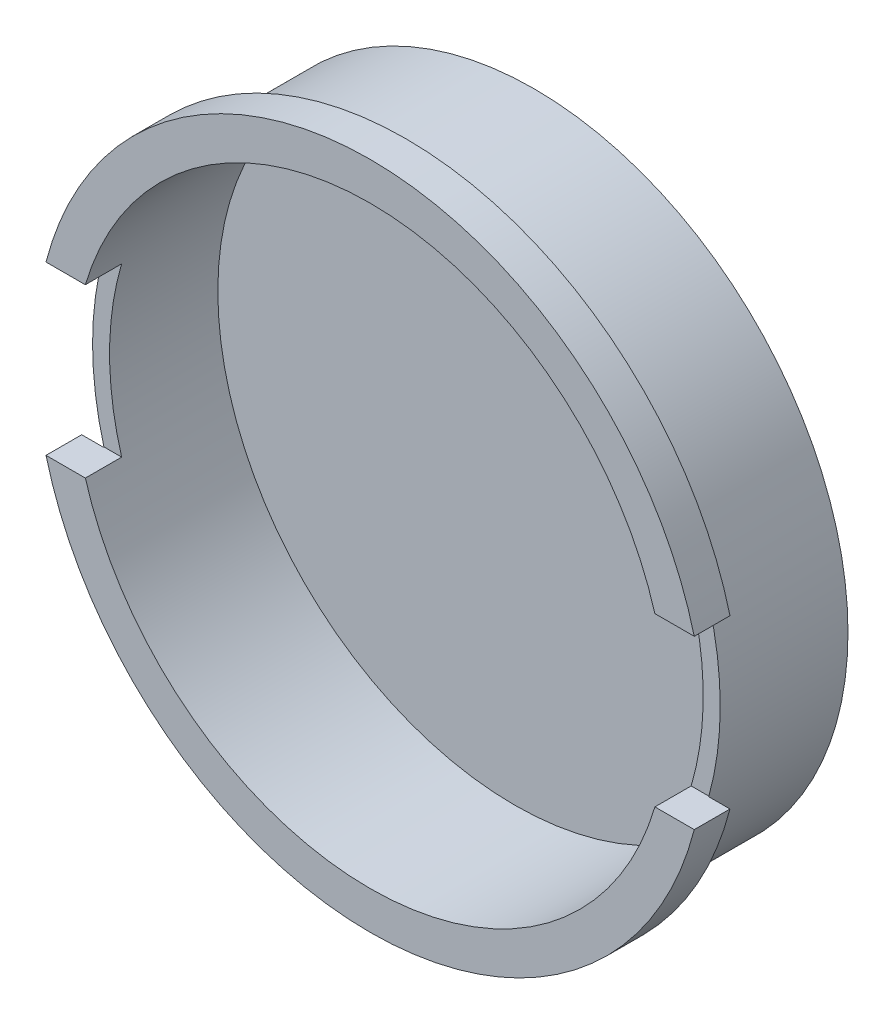
SolidWorks part; units mm, degrees
material "Chrome Stainless Steel"
ref_plane "Front Plane" through (0, 0, 0) normal (0, 0, 1) x (1, 0, 0)
ref_plane "Top Plane" through (0, 0, 0) normal (0, 1, 0) x (1, 0, 0)
ref_plane "Right Plane" through (0, 0, 0) normal (1, 0, 0) x (0, 0, -1)
sketch "Sketch1" plane through (0, 0, 0) normal (0, 0, 1) x (1, 0, 0)
  circle A0 centre (0, 0) radius 14.2875
  dimension "D1" = 28.575
extrude "Boss-Extrude1" add sketch "Sketch1" along normal blind 0.889
sketch "Sketch2" plane through (0, 0, 0.889) normal (0, 0, 1) x (1, 0, 0)
  circle A0 centre (0, 0) radius 13.5128
  circle A1 centre (0, 0) radius 14.2875
  dimension "D1" = 27.0256
  dimension "D2" = 28.575
extrude "Boss-Extrude2" add sketch "Sketch2" along normal blind 4.953
sketch "Sketch3" plane through (0, 0, 5.842) normal (0, 0, 1) x (1, 0, 0)
  circle A0 centre (0, 0) radius 15.24
  circle A1 centre (0, 0) radius 13.5128
extrude "Boss-Extrude3" add sketch "Sketch3" along normal blind 1.6256
sketch "Sketch4" plane through (0, 0, 7.4676) normal (0, 0, 1) x (1, 0, 0)
  line L1 (-19.05, 3.81) -> (19.05, 3.81)
  line L2 (-19.05, 3.81) -> (-19.05, -3.81)
  line L3 (-19.05, -3.81) -> (19.05, -3.81)
  line L4 (19.05, 3.81) -> (19.05, -3.81)
  line L5 (-19.05, 3.81) -> (19.05, -3.81) construction
  line L6 (-19.05, -3.81) -> (19.05, 3.81) construction
  point P0 (0, 0)
  dimension "D1" = 38.1
  dimension "D2" = 7.62
extrude "Cut-Extrude1" cut sketch "Sketch4" against normal blind 1.651
sketch "Sketch5" plane through (0, 0, 7.4426) normal (0, 0, 1) x (1, 0, 0)
  line L0 (-0.8, 12.3) -> (-0.8, 13.1) construction
  line L1 (0.8, 13.1) -> (0.8, 12.3) construction
  line L2 (-2.1761, 0.4523) -> (-2.7495, 3.7042)
  line L3 (-3.3999, 3.5895) -> (-2.8265, 0.3376)
  line L4 (-2.1761, 0.4523) -> (-2.7495, 3.7042)
  line L5 (-3.3999, 3.5895) -> (-2.8265, 0.3376)
  line L18 (-6.4001, -3.8435) -> (-6.9735, -0.5916)
  line L19 (-7.6239, -0.7063) -> (-7.0505, -3.9582)
  line L20 (-6.4001, -3.8435) -> (-6.9735, -0.5916)
  line L21 (-7.6239, -0.7063) -> (-7.0505, -3.9582)
  line L22 (-1.4003, -3.9477) -> (-1.9737, -0.6958)
  line L23 (-2.624, -0.8105) -> (-2.0506, -4.0624)
  line L24 (-1.4003, -3.9477) -> (-1.9737, -0.6958)
  line L25 (-2.624, -0.8105) -> (-2.0506, -4.0624)
  line L26 (-7.176, 0.5565) -> (-7.7494, 3.8084)
  line L27 (-8.3997, 3.6937) -> (-7.8263, 0.4418)
  line L28 (-7.176, 0.5565) -> (-7.7494, 3.8084)
  line L29 (-8.3997, 3.6937) -> (-7.8263, 0.4418)
  line L30 (-3.376, 0.2032) -> (-6.424, 0.2032)
  line L31 (-6.424, -0.4572) -> (-3.376, -0.4572)
  line L32 (-3.376, 0.2032) -> (-6.424, 0.2032)
  line L33 (-6.424, -0.4572) -> (-3.376, -0.4572)
  line L34 (-2.6002, -4.1968) -> (-5.6482, -4.1968)
  line L35 (-5.6482, -4.8572) -> (-2.6002, -4.8572)
  line L36 (-2.6002, -4.1968) -> (-5.6482, -4.1968)
  line L37 (-5.6482, -4.8572) -> (-2.6002, -4.8572)
  line L38 (-4.1518, 4.6032) -> (-7.1998, 4.6032)
  line L39 (-7.1998, 3.9428) -> (-4.1518, 3.9428)
  line L40 (-4.1518, 4.6032) -> (-7.1998, 4.6032)
  line L41 (-7.1998, 3.9428) -> (-4.1518, 3.9428)
  line L42 (7.6239, 0.4523) -> (7.0505, 3.7042)
  line L43 (6.4001, 3.5895) -> (6.9735, 0.3376)
  line L44 (7.6239, 0.4523) -> (7.0505, 3.7042)
  line L45 (6.4001, 3.5895) -> (6.9735, 0.3376)
  line L46 (3.3999, -3.8435) -> (2.8265, -0.5916)
  line L47 (2.1761, -0.7063) -> (2.7495, -3.9582)
  line L48 (3.3999, -3.8435) -> (2.8265, -0.5916)
  line L49 (2.1761, -0.7063) -> (2.7495, -3.9582)
  line L50 (8.3997, -3.9477) -> (7.8263, -0.6958)
  line L51 (7.176, -0.8105) -> (7.7494, -4.0624)
  line L52 (8.3997, -3.9477) -> (7.8263, -0.6958)
  line L53 (7.176, -0.8105) -> (7.7494, -4.0624)
  line L54 (2.624, 0.5565) -> (2.0506, 3.8084)
  line L55 (1.4003, 3.6937) -> (1.9737, 0.4418)
  line L56 (2.624, 0.5565) -> (2.0506, 3.8084)
  line L57 (1.4003, 3.6937) -> (1.9737, 0.4418)
  line L58 (6.424, 0.2032) -> (3.376, 0.2032)
  line L59 (3.376, -0.4572) -> (6.424, -0.4572)
  line L60 (6.424, 0.2032) -> (3.376, 0.2032)
  line L61 (3.376, -0.4572) -> (6.424, -0.4572)
  line L62 (7.1998, -4.1968) -> (4.1518, -4.1968)
  line L63 (4.1518, -4.8572) -> (7.1998, -4.8572)
  line L64 (7.1998, -4.1968) -> (4.1518, -4.1968)
  line L65 (4.1518, -4.8572) -> (7.1998, -4.8572)
  line L66 (5.6482, 4.6032) -> (2.6002, 4.6032)
  line L67 (2.6002, 3.9428) -> (5.6482, 3.9428)
  line L68 (5.6482, 4.6032) -> (2.6002, 4.6032)
  line L69 (2.6002, 3.9428) -> (5.6482, 3.9428)
  line L70 (-0.8, 13.1) -> (0.8, 13.1) construction
  line L71 (0.8, 12.3) -> (-0.8, 12.3) construction
  line L72 (-0.8, 12.3) -> (-0.8, 13.1) construction
  line L73 (0.8, 13.1) -> (0.8, 12.3) construction
  line L74 (-0.8, 13.1) -> (0.8, 13.1) construction
  line L75 (0.8, 12.3) -> (-0.8, 12.3) construction
  circle A0 centre (0, 12.7) radius 0.381
  circle A1 centre (4.8601, 11.7333) radius 0.381
  circle A2 centre (8.9803, 8.9803) radius 0.381
  circle A3 centre (11.7333, 4.8601) radius 0.381
  circle A4 centre (12.7, 0) radius 0.381
  circle A5 centre (11.7333, -4.8601) radius 0.381
  arc A6 (-2.7495, 3.7042) -> (-3.3999, 3.5895) centre (-3.0747, 3.6468) ccw
  arc A7 (-2.8265, 0.3376) -> (-2.1761, 0.4523) centre (-2.5013, 0.395) ccw
  arc A8 (-2.7495, 3.7042) -> (-3.3999, 3.5895) centre (-3.0747, 3.6468) ccw
  arc A9 (-2.8265, 0.3376) -> (-2.1761, 0.4523) centre (-2.5013, 0.395) ccw
  arc A10 (-6.9735, -0.5916) -> (-7.6239, -0.7063) centre (-7.2987, -0.649) ccw
  arc A11 (-7.0505, -3.9582) -> (-6.4001, -3.8435) centre (-6.7253, -3.9008) ccw
  arc A12 (-6.9735, -0.5916) -> (-7.6239, -0.7063) centre (-7.2987, -0.649) ccw
  arc A13 (-7.0505, -3.9582) -> (-6.4001, -3.8435) centre (-6.7253, -3.9008) ccw
  arc A14 (-1.9737, -0.6958) -> (-2.624, -0.8105) centre (-2.2988, -0.7532) ccw
  arc A15 (-2.0506, -4.0624) -> (-1.4003, -3.9477) centre (-1.7255, -4.005) ccw
  arc A16 (-1.9737, -0.6958) -> (-2.624, -0.8105) centre (-2.2988, -0.7532) ccw
  arc A17 (-2.0506, -4.0624) -> (-1.4003, -3.9477) centre (-1.7255, -4.005) ccw
  arc A18 (-7.8263, 0.4418) -> (-7.176, 0.5565) centre (-7.5012, 0.4992) ccw
  arc A19 (-7.7494, 3.8084) -> (-8.3997, 3.6937) centre (-8.0745, 3.751) ccw
  arc A20 (-7.8263, 0.4418) -> (-7.176, 0.5565) centre (-7.5012, 0.4992) ccw
  arc A21 (-7.7494, 3.8084) -> (-8.3997, 3.6937) centre (-8.0745, 3.751) ccw
  arc A22 (-6.424, 0.2032) -> (-6.424, -0.4572) centre (-6.424, -0.127) ccw
  arc A23 (-3.376, -0.4572) -> (-3.376, 0.2032) centre (-3.376, -0.127) ccw
  arc A24 (-6.424, 0.2032) -> (-6.424, -0.4572) centre (-6.424, -0.127) ccw
  arc A25 (-3.376, -0.4572) -> (-3.376, 0.2032) centre (-3.376, -0.127) ccw
  arc A26 (-5.6482, -4.1968) -> (-5.6482, -4.8572) centre (-5.6482, -4.527) ccw
  arc A27 (-2.6002, -4.8572) -> (-2.6002, -4.1968) centre (-2.6002, -4.527) ccw
  arc A28 (-5.6482, -4.1968) -> (-5.6482, -4.8572) centre (-5.6482, -4.527) ccw
  arc A29 (-2.6002, -4.8572) -> (-2.6002, -4.1968) centre (-2.6002, -4.527) ccw
  arc A30 (-7.1998, 4.6032) -> (-7.1998, 3.9428) centre (-7.1998, 4.273) ccw
  arc A31 (-4.1518, 3.9428) -> (-4.1518, 4.6032) centre (-4.1518, 4.273) ccw
  arc A32 (-7.1998, 4.6032) -> (-7.1998, 3.9428) centre (-7.1998, 4.273) ccw
  arc A33 (-4.1518, 3.9428) -> (-4.1518, 4.6032) centre (-4.1518, 4.273) ccw
  arc A34 (7.0505, 3.7042) -> (6.4001, 3.5895) centre (6.7253, 3.6468) ccw
  arc A35 (6.9735, 0.3376) -> (7.6239, 0.4523) centre (7.2987, 0.395) ccw
  arc A36 (7.0505, 3.7042) -> (6.4001, 3.5895) centre (6.7253, 3.6468) ccw
  arc A37 (6.9735, 0.3376) -> (7.6239, 0.4523) centre (7.2987, 0.395) ccw
  arc A38 (2.8265, -0.5916) -> (2.1761, -0.7063) centre (2.5013, -0.649) ccw
  arc A39 (2.7495, -3.9582) -> (3.3999, -3.8435) centre (3.0747, -3.9008) ccw
  arc A40 (2.8265, -0.5916) -> (2.1761, -0.7063) centre (2.5013, -0.649) ccw
  arc A41 (2.7495, -3.9582) -> (3.3999, -3.8435) centre (3.0747, -3.9008) ccw
  arc A42 (7.8263, -0.6958) -> (7.176, -0.8105) centre (7.5012, -0.7532) ccw
  arc A43 (7.7494, -4.0624) -> (8.3997, -3.9477) centre (8.0745, -4.005) ccw
  arc A44 (7.8263, -0.6958) -> (7.176, -0.8105) centre (7.5012, -0.7532) ccw
  arc A45 (7.7494, -4.0624) -> (8.3997, -3.9477) centre (8.0745, -4.005) ccw
  arc A46 (1.9737, 0.4418) -> (2.624, 0.5565) centre (2.2988, 0.4992) ccw
  arc A47 (2.0506, 3.8084) -> (1.4003, 3.6937) centre (1.7255, 3.751) ccw
  arc A48 (1.9737, 0.4418) -> (2.624, 0.5565) centre (2.2988, 0.4992) ccw
  arc A49 (2.0506, 3.8084) -> (1.4003, 3.6937) centre (1.7255, 3.751) ccw
  arc A50 (3.376, 0.2032) -> (3.376, -0.4572) centre (3.376, -0.127) ccw
  arc A51 (6.424, -0.4572) -> (6.424, 0.2032) centre (6.424, -0.127) ccw
  arc A52 (3.376, 0.2032) -> (3.376, -0.4572) centre (3.376, -0.127) ccw
  arc A53 (6.424, -0.4572) -> (6.424, 0.2032) centre (6.424, -0.127) ccw
  arc A54 (4.1518, -4.1968) -> (4.1518, -4.8572) centre (4.1518, -4.527) ccw
  arc A55 (7.1998, -4.8572) -> (7.1998, -4.1968) centre (7.1998, -4.527) ccw
  arc A56 (4.1518, -4.1968) -> (4.1518, -4.8572) centre (4.1518, -4.527) ccw
  arc A57 (7.1998, -4.8572) -> (7.1998, -4.1968) centre (7.1998, -4.527) ccw
  arc A58 (2.6002, 4.6032) -> (2.6002, 3.9428) centre (2.6002, 4.273) ccw
  arc A59 (5.6482, 3.9428) -> (5.6482, 4.6032) centre (5.6482, 4.273) ccw
  arc A60 (2.6002, 4.6032) -> (2.6002, 3.9428) centre (2.6002, 4.273) ccw
  arc A61 (5.6482, 3.9428) -> (5.6482, 4.6032) centre (5.6482, 4.273) ccw
  circle A62 centre (8.9803, -8.9803) radius 0.381
  circle A63 centre (4.8601, -11.7333) radius 0.381
  circle A64 centre (0, -12.7) radius 0.381
  circle A65 centre (-4.8601, -11.7333) radius 0.381
  circle A66 centre (-8.9803, -8.9803) radius 0.381
  circle A67 centre (-11.7333, -4.8601) radius 0.381
  circle A68 centre (-12.7, 0) radius 0.381
  circle A69 centre (-11.7333, 4.8601) radius 0.381
  circle A70 centre (-8.9803, 8.9803) radius 0.381
  circle A71 centre (-4.8601, 11.7333) radius 0.381
  point P90 (0, 12.7)
  point P124 (0, 0)
  dimension "D16" = 0.762
  dimension "D2" = 0
  dimension "D3" = 0
  dimension "D4" = 0
  dimension "D5" = 0
  dimension "D6" = 0
  dimension "D7" = 0
  dimension "D8" = 0
  dimension "D9" = 0
  dimension "D10" = 0
  dimension "D11" = 0
  dimension "D12" = 0
  dimension "D13" = 0
  dimension "D14" = 0
  dimension "D15" = 0
  dimension "D17" = 16
extrude "Cut-Extrude2" cut sketch "Sketch5" against normal through all
sketch "Sketch7" plane through (0, 0, 0.889) normal (0, 0, -1) x (-1, 0, 0)
  line L2 (2.7495, 3.7042) -> (2.1761, 0.4523)
  line L3 (2.8265, 0.3376) -> (3.3999, 3.5895)
  line L4 (2.7495, 3.7042) -> (2.1761, 0.4523)
  line L5 (2.8265, 0.3376) -> (3.3999, 3.5895)
  line L6 (1.9737, -0.6958) -> (1.4003, -3.9477)
  line L7 (2.0506, -4.0624) -> (2.624, -0.8105)
  line L8 (1.9737, -0.6958) -> (1.4003, -3.9477)
  line L9 (2.0506, -4.0624) -> (2.624, -0.8105)
  line L10 (7.0505, -3.9582) -> (7.6239, -0.7063)
  line L11 (6.9735, -0.5916) -> (6.4001, -3.8435)
  line L12 (7.0505, -3.9582) -> (7.6239, -0.7063)
  line L13 (6.9735, -0.5916) -> (6.4001, -3.8435)
  line L14 (5.6482, -4.1968) -> (2.6002, -4.1968)
  line L15 (2.6002, -4.8572) -> (5.6482, -4.8572)
  line L16 (5.6482, -4.1968) -> (2.6002, -4.1968)
  line L17 (2.6002, -4.8572) -> (5.6482, -4.8572)
  line L18 (6.424, 0.2032) -> (3.376, 0.2032)
  line L19 (3.376, -0.4572) -> (6.424, -0.4572)
  line L20 (6.424, 0.2032) -> (3.376, 0.2032)
  line L21 (3.376, -0.4572) -> (6.424, -0.4572)
  line L22 (7.7494, 3.8084) -> (7.176, 0.5565)
  line L23 (7.8263, 0.4418) -> (8.3997, 3.6937)
  line L24 (7.7494, 3.8084) -> (7.176, 0.5565)
  line L25 (7.8263, 0.4418) -> (8.3997, 3.6937)
  line L26 (-2.8265, -0.5916) -> (-3.3999, -3.8435)
  line L27 (-2.7495, -3.9582) -> (-2.1761, -0.7063)
  line L28 (-2.8265, -0.5916) -> (-3.3999, -3.8435)
  line L29 (-2.7495, -3.9582) -> (-2.1761, -0.7063)
  line L30 (-7.0505, 3.7042) -> (-7.6239, 0.4523)
  line L31 (-6.9735, 0.3376) -> (-6.4001, 3.5895)
  line L32 (-7.0505, 3.7042) -> (-7.6239, 0.4523)
  line L33 (-6.9735, 0.3376) -> (-6.4001, 3.5895)
  line L34 (4.1518, 3.9428) -> (7.1998, 3.9428)
  line L35 (7.1998, 4.6032) -> (4.1518, 4.6032)
  line L36 (4.1518, 3.9428) -> (7.1998, 3.9428)
  line L37 (7.1998, 4.6032) -> (4.1518, 4.6032)
  line L38 (-2.0506, 3.8084) -> (-2.624, 0.5565)
  line L39 (-1.9737, 0.4418) -> (-1.4003, 3.6937)
  line L40 (-2.0506, 3.8084) -> (-2.624, 0.5565)
  line L41 (-1.9737, 0.4418) -> (-1.4003, 3.6937)
  line L42 (-7.7494, -4.0624) -> (-7.176, -0.8105)
  line L43 (-7.8263, -0.6958) -> (-8.3997, -3.9477)
  line L44 (-7.7494, -4.0624) -> (-7.176, -0.8105)
  line L45 (-7.8263, -0.6958) -> (-8.3997, -3.9477)
  line L46 (-2.6002, 4.6032) -> (-5.6482, 4.6032)
  line L47 (-5.6482, 3.9428) -> (-2.6002, 3.9428)
  line L48 (-2.6002, 4.6032) -> (-5.6482, 4.6032)
  line L49 (-5.6482, 3.9428) -> (-2.6002, 3.9428)
  line L50 (-4.1518, -4.1968) -> (-7.1998, -4.1968)
  line L51 (-7.1998, -4.8572) -> (-4.1518, -4.8572)
  line L52 (-4.1518, -4.1968) -> (-7.1998, -4.1968)
  line L53 (-7.1998, -4.8572) -> (-4.1518, -4.8572)
  line L54 (-3.376, 0.2032) -> (-6.424, 0.2032)
  line L55 (-6.424, -0.4572) -> (-3.376, -0.4572)
  line L56 (-3.376, 0.2032) -> (-6.424, 0.2032)
  line L57 (-6.424, -0.4572) -> (-3.376, -0.4572)
  circle A1 centre (-11.7333, 4.8601) radius 0.381
  circle A2 centre (-11.7333, 4.8601) radius 0.381
  circle A3 centre (-8.9803, 8.9803) radius 0.381
  circle A4 centre (-8.9803, 8.9803) radius 0.381
  circle A5 centre (-4.8601, 11.7333) radius 0.381
  circle A6 centre (-4.8601, 11.7333) radius 0.381
  circle A7 centre (0, 12.7) radius 0.381
  circle A8 centre (0, 12.7) radius 0.381
  circle A9 centre (4.8601, -11.7333) radius 0.381
  arc A10 (3.3999, 3.5895) -> (2.7495, 3.7042) centre (3.0747, 3.6468) ccw
  arc A11 (2.1761, 0.4523) -> (2.8265, 0.3376) centre (2.5013, 0.395) ccw
  arc A12 (3.3999, 3.5895) -> (2.7495, 3.7042) centre (3.0747, 3.6468) ccw
  arc A13 (2.1761, 0.4523) -> (2.8265, 0.3376) centre (2.5013, 0.395) ccw
  arc A14 (2.624, -0.8105) -> (1.9737, -0.6958) centre (2.2988, -0.7532) ccw
  arc A15 (1.4003, -3.9477) -> (2.0506, -4.0624) centre (1.7255, -4.005) ccw
  arc A16 (2.624, -0.8105) -> (1.9737, -0.6958) centre (2.2988, -0.7532) ccw
  arc A17 (1.4003, -3.9477) -> (2.0506, -4.0624) centre (1.7255, -4.005) ccw
  arc A18 (6.4001, -3.8435) -> (7.0505, -3.9582) centre (6.7253, -3.9008) ccw
  arc A19 (7.6239, -0.7063) -> (6.9735, -0.5916) centre (7.2987, -0.649) ccw
  arc A20 (6.4001, -3.8435) -> (7.0505, -3.9582) centre (6.7253, -3.9008) ccw
  arc A21 (7.6239, -0.7063) -> (6.9735, -0.5916) centre (7.2987, -0.649) ccw
  arc A22 (5.6482, -4.8572) -> (5.6482, -4.1968) centre (5.6482, -4.527) ccw
  arc A23 (2.6002, -4.1968) -> (2.6002, -4.8572) centre (2.6002, -4.527) ccw
  arc A24 (5.6482, -4.8572) -> (5.6482, -4.1968) centre (5.6482, -4.527) ccw
  arc A25 (2.6002, -4.1968) -> (2.6002, -4.8572) centre (2.6002, -4.527) ccw
  arc A26 (3.376, 0.2032) -> (3.376, -0.4572) centre (3.376, -0.127) ccw
  arc A27 (6.424, -0.4572) -> (6.424, 0.2032) centre (6.424, -0.127) ccw
  arc A28 (3.376, 0.2032) -> (3.376, -0.4572) centre (3.376, -0.127) ccw
  arc A29 (6.424, -0.4572) -> (6.424, 0.2032) centre (6.424, -0.127) ccw
  arc A30 (8.3997, 3.6937) -> (7.7494, 3.8084) centre (8.0745, 3.751) ccw
  arc A31 (7.176, 0.5565) -> (7.8263, 0.4418) centre (7.5012, 0.4992) ccw
  arc A32 (8.3997, 3.6937) -> (7.7494, 3.8084) centre (8.0745, 3.751) ccw
  arc A33 (7.176, 0.5565) -> (7.8263, 0.4418) centre (7.5012, 0.4992) ccw
  arc A34 (-2.1761, -0.7063) -> (-2.8265, -0.5916) centre (-2.5013, -0.649) ccw
  arc A35 (-3.3999, -3.8435) -> (-2.7495, -3.9582) centre (-3.0747, -3.9008) ccw
  arc A36 (-2.1761, -0.7063) -> (-2.8265, -0.5916) centre (-2.5013, -0.649) ccw
  arc A37 (-3.3999, -3.8435) -> (-2.7495, -3.9582) centre (-3.0747, -3.9008) ccw
  arc A38 (-6.4001, 3.5895) -> (-7.0505, 3.7042) centre (-6.7253, 3.6468) ccw
  arc A39 (-7.6239, 0.4523) -> (-6.9735, 0.3376) centre (-7.2987, 0.395) ccw
  arc A40 (-6.4001, 3.5895) -> (-7.0505, 3.7042) centre (-6.7253, 3.6468) ccw
  arc A41 (-7.6239, 0.4523) -> (-6.9735, 0.3376) centre (-7.2987, 0.395) ccw
  arc A42 (4.1518, 4.6032) -> (4.1518, 3.9428) centre (4.1518, 4.273) ccw
  arc A43 (7.1998, 3.9428) -> (7.1998, 4.6032) centre (7.1998, 4.273) ccw
  arc A44 (4.1518, 4.6032) -> (4.1518, 3.9428) centre (4.1518, 4.273) ccw
  arc A45 (7.1998, 3.9428) -> (7.1998, 4.6032) centre (7.1998, 4.273) ccw
  arc A46 (-1.4003, 3.6937) -> (-2.0506, 3.8084) centre (-1.7255, 3.751) ccw
  arc A47 (-2.624, 0.5565) -> (-1.9737, 0.4418) centre (-2.2988, 0.4992) ccw
  arc A48 (-1.4003, 3.6937) -> (-2.0506, 3.8084) centre (-1.7255, 3.751) ccw
  arc A49 (-2.624, 0.5565) -> (-1.9737, 0.4418) centre (-2.2988, 0.4992) ccw
  arc A50 (-8.3997, -3.9477) -> (-7.7494, -4.0624) centre (-8.0745, -4.005) ccw
  arc A51 (-7.176, -0.8105) -> (-7.8263, -0.6958) centre (-7.5012, -0.7532) ccw
  arc A52 (-8.3997, -3.9477) -> (-7.7494, -4.0624) centre (-8.0745, -4.005) ccw
  arc A53 (-7.176, -0.8105) -> (-7.8263, -0.6958) centre (-7.5012, -0.7532) ccw
  arc A54 (-2.6002, 3.9428) -> (-2.6002, 4.6032) centre (-2.6002, 4.273) ccw
  arc A55 (-5.6482, 4.6032) -> (-5.6482, 3.9428) centre (-5.6482, 4.273) ccw
  arc A56 (-2.6002, 3.9428) -> (-2.6002, 4.6032) centre (-2.6002, 4.273) ccw
  arc A57 (-5.6482, 4.6032) -> (-5.6482, 3.9428) centre (-5.6482, 4.273) ccw
  arc A58 (-7.1998, -4.1968) -> (-7.1998, -4.8572) centre (-7.1998, -4.527) ccw
  arc A59 (-4.1518, -4.8572) -> (-4.1518, -4.1968) centre (-4.1518, -4.527) ccw
  arc A60 (-7.1998, -4.1968) -> (-7.1998, -4.8572) centre (-7.1998, -4.527) ccw
  arc A61 (-4.1518, -4.8572) -> (-4.1518, -4.1968) centre (-4.1518, -4.527) ccw
  arc A62 (-3.376, -0.4572) -> (-3.376, 0.2032) centre (-3.376, -0.127) ccw
  arc A63 (-6.424, 0.2032) -> (-6.424, -0.4572) centre (-6.424, -0.127) ccw
  arc A64 (-3.376, -0.4572) -> (-3.376, 0.2032) centre (-3.376, -0.127) ccw
  arc A65 (-6.424, 0.2032) -> (-6.424, -0.4572) centre (-6.424, -0.127) ccw
  circle A66 centre (4.8601, -11.7333) radius 0.381
  circle A67 centre (0, -12.7) radius 0.381
  circle A68 centre (0, -12.7) radius 0.381
  circle A69 centre (-4.8601, -11.7333) radius 0.381
  circle A70 centre (-4.8601, -11.7333) radius 0.381
  circle A71 centre (-8.9803, -8.9803) radius 0.381
  circle A72 centre (-8.9803, -8.9803) radius 0.381
  circle A73 centre (-11.7333, -4.8601) radius 0.381
  circle A74 centre (-11.7333, -4.8601) radius 0.381
  circle A75 centre (-12.7, 0) radius 0.381
  circle A76 centre (-12.7, 0) radius 0.381
  circle A77 centre (4.8601, 11.7333) radius 0.381
  circle A78 centre (4.8601, 11.7333) radius 0.381
  circle A79 centre (8.9803, 8.9803) radius 0.381
  circle A80 centre (8.9803, 8.9803) radius 0.381
  circle A81 centre (11.7333, 4.8601) radius 0.381
  circle A82 centre (11.7333, 4.8601) radius 0.381
  circle A83 centre (12.7, 0) radius 0.381
  circle A84 centre (12.7, 0) radius 0.381
  circle A85 centre (11.7333, -4.8601) radius 0.381
  circle A86 centre (11.7333, -4.8601) radius 0.381
  circle A87 centre (8.9803, -8.9803) radius 0.381
  circle A88 centre (8.9803, -8.9803) radius 0.381
  dimension "D1" = 0
  dimension "D2" = 0
  dimension "D3" = 0
  dimension "D4" = 0
  dimension "D5" = 0
  dimension "D6" = 0
  dimension "D7" = 0
  dimension "D8" = 0
  dimension "D9" = 0
  dimension "D10" = 0
  dimension "D11" = 0
  dimension "D12" = 0
  dimension "D13" = 0
  dimension "D14" = 0
  dimension "D15" = 0
  dimension "D16" = 0
  dimension "D17" = 0
  dimension "D18" = 0
  dimension "D19" = 0
  dimension "D20" = 0
  dimension "D21" = 0
  dimension "D22" = 0
  dimension "D23" = 0
  dimension "D24" = 0
  dimension "D25" = 0
  dimension "D26" = 0
  dimension "D27" = 0
  dimension "D28" = 0
  dimension "D29" = 0
  dimension "D30" = 0
extrude "Boss-Extrude5" add sketch "Sketch7" along normal blind 0.9144
